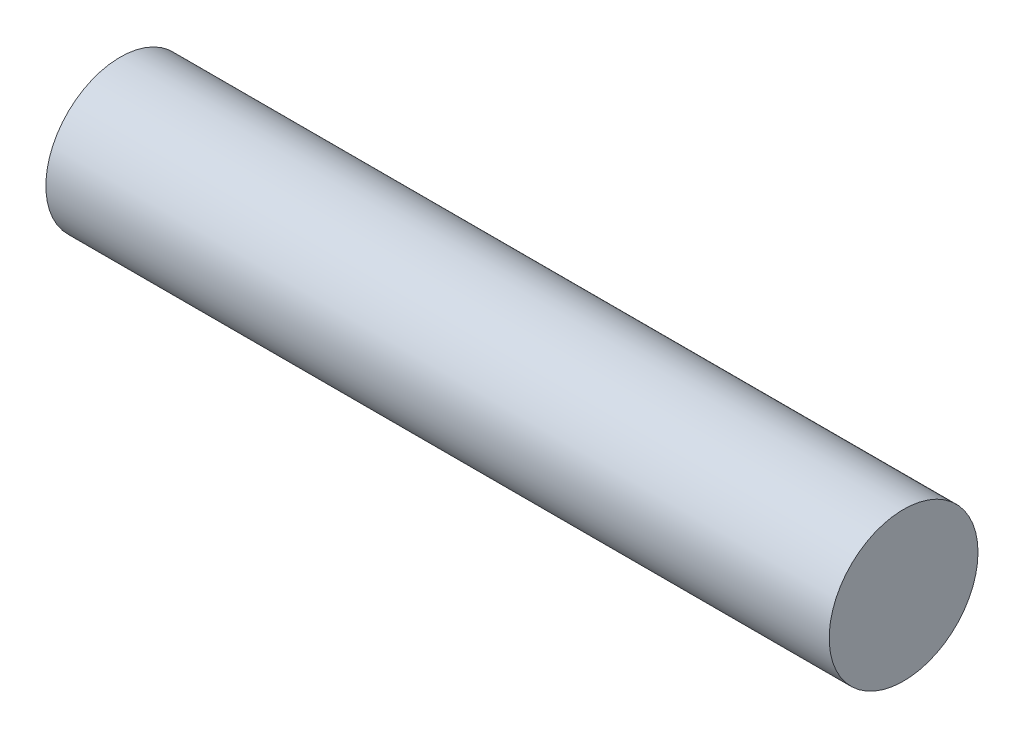
SolidWorks part; units mm, degrees
material "Plain Carbon Steel"
ref_plane "Front Plane" through (0, 0, 0) normal (0, 0, 1) x (1, 0, 0)
ref_plane "Top Plane" through (0, 0, 0) normal (0, 1, 0) x (1, 0, 0)
ref_plane "Right Plane" through (0, 0, 0) normal (1, 0, 0) x (0, 0, -1)
sketch "Sketch2" plane through (0, 0, 0) normal (1, 0, 0) x (0, 0, -1)
  circle A0 centre (0, 0) radius 0.95
  dimension "D1" = 1.9
extrude "Boss-Extrude1" add sketch "Sketch2" along normal blind 10
